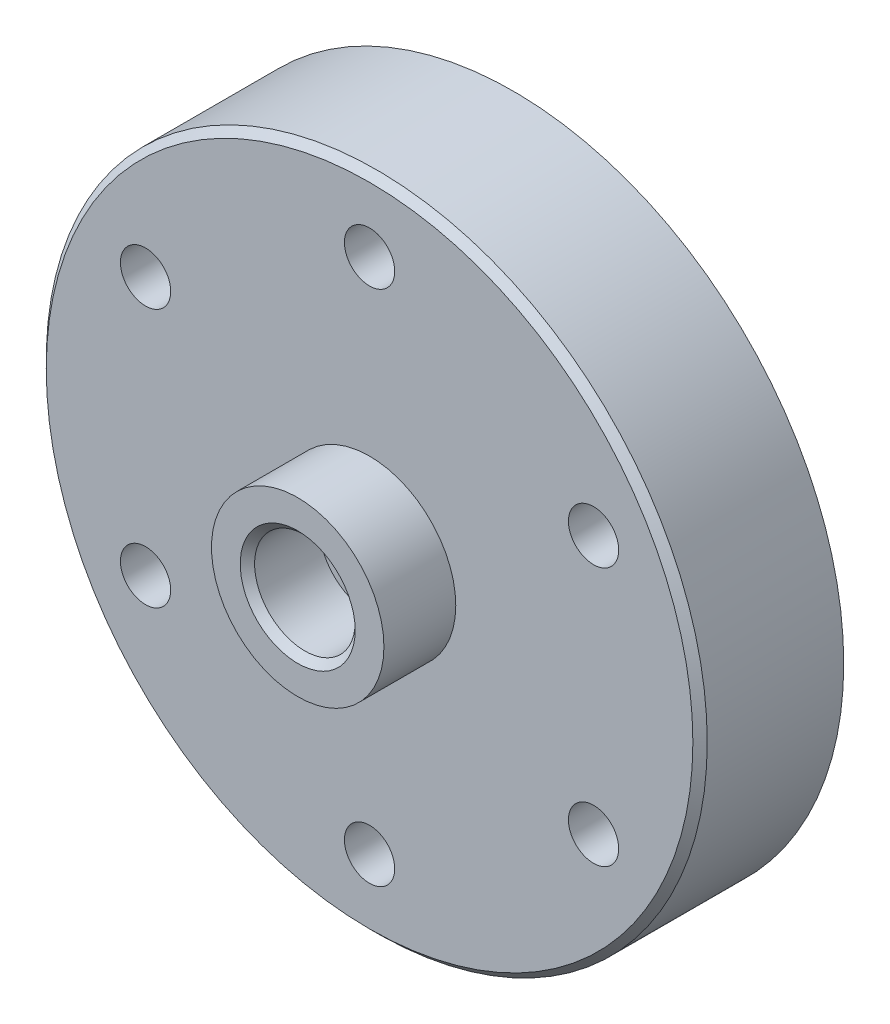
SolidWorks part; units mm, degrees
ref_plane "Front Plane" through (0, 0, 0) normal (0, 0, 1) x (1, 0, 0)
ref_plane "Top Plane" through (0, 0, 0) normal (0, 1, 0) x (1, 0, 0)
ref_plane "Right Plane" through (0, 0, 0) normal (1, 0, 0) x (0, 0, -1)
sketch "Sketch1" plane through (0, 0, 0) normal (0, 0, 1) x (1, 0, 0)
  circle A0 centre (0, 0) radius 46
  circle A1 centre (0, 0) radius 36 construction
  circle A2 centre (0, 36) radius 3.5
  circle A3 centre (31.1769, 18) radius 3.5
  circle A4 centre (31.1769, -18) radius 3.5
  circle A5 centre (0, -36) radius 3.5
  circle A6 centre (-31.1769, -18) radius 3.5
  circle A7 centre (-31.1769, 18) radius 3.5
  point P19 (0, 0)
  dimension "D1" = 72
  dimension "D2" = 92
  dimension "D3" = 7
  dimension "D4" = 6
extrude "Boss-Extrude1" add sketch "Sketch1" along normal blind 20
chamfer "Chamfer1" distance 1 angle 45 1 edges at (46, 0, 20)
sketch "Sketch2" plane through (0, 0, 20) normal (0, 0, 1) x (1, 0, 0)
  circle A0 centre (0, 0) radius 12
  dimension "D1" = 24
extrude "Boss-Extrude2" add sketch "Sketch2" along normal blind 10
sketch "Sketch3" plane through (0, 0, 0) normal (0, 0, -1) x (-1, 0, 0)
  circle A0 centre (0, 0) radius 33
  dimension "D1" = 66
extrude "Cut-Extrude1" cut sketch "Sketch3" against normal blind 14
sketch "Sketch4" plane through (0, 0, 14) normal (0, 0, -1) x (-1, 0, 0)
  circle A0 centre (0, 0) radius 2.5
  dimension "D1" = 5
extrude "Cut-Extrude2" cut sketch "Sketch4" against normal blind 6
sketch "Sketch5" plane through (0, 0, 30) normal (0, 0, 1) x (1, 0, 0)
  circle A0 centre (0, 0) radius 7
  dimension "D1" = 14
extrude "Cut-Extrude3" cut sketch "Sketch5" against normal blind 10
cosmetic thread "Cosmetic Thread1" parameters "D1"=10, "D2"=16
chamfer "Chamfer2" distance 1 angle 45 1 edges at (7, 0, 30)
sketch "Sketch6" plane through (0, 0, 0) normal (1, 0, 0) x (0, 0, -1)
  circle A0 centre (-8, 0) radius 4
  dimension "D1" = 8
  dimension "D2" = 8
extrude "Cut-Extrude4" cut sketch "Sketch6" against normal blind 80
